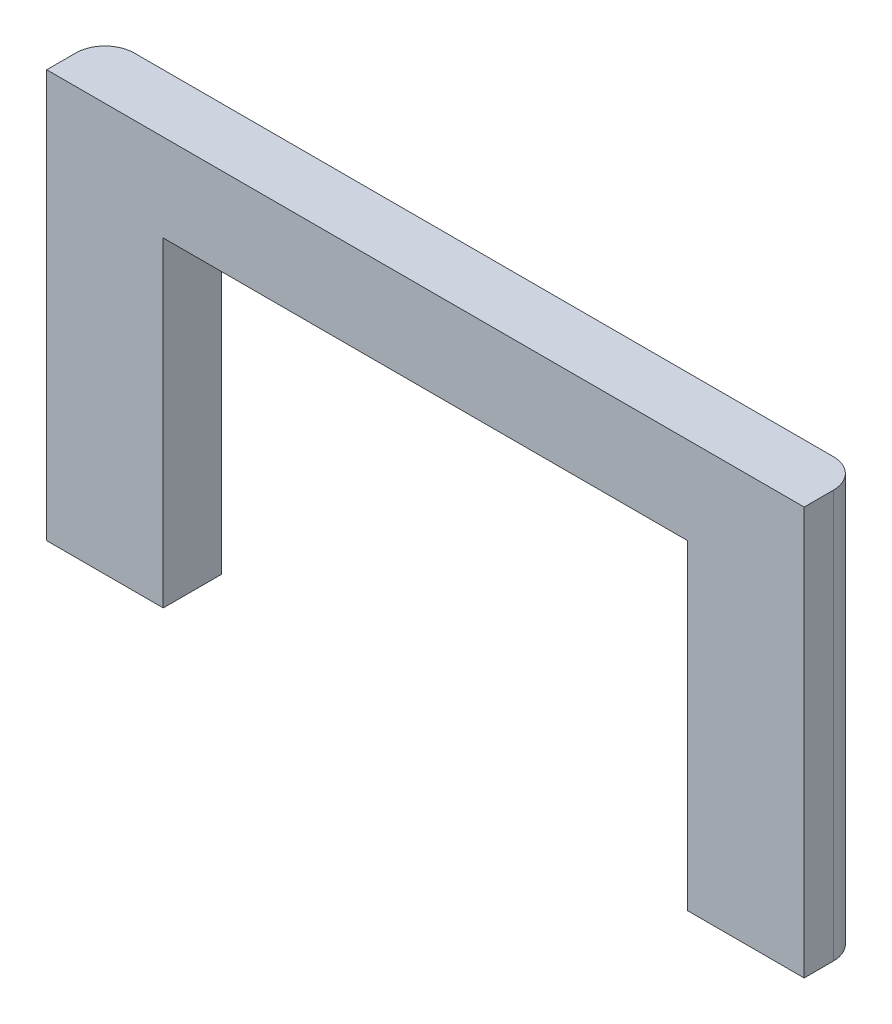
SolidWorks part; units mm, degrees
ref_plane "Front" through (0, 0, 0) normal (0, 0, 1) x (1, 0, 0)
ref_plane "Top" through (0, 0, 0) normal (0, 1, 0) x (1, 0, 0)
ref_plane "Right" through (0, 0, 0) normal (1, 0, 0) x (0, 0, -1)
sketch "Esquisse1" plane through (0, 0, 0) normal (0, 0, 1) x (1, 0, 0)
  line L1 (-83.304, 29.9119) -> (46.696, 29.9119)
  line L2 (-83.304, 29.9119) -> (-83.304, -40.0881)
  line L3 (-83.304, -40.0881) -> (-63.304, -40.0881)
  line L4 (46.696, 29.9119) -> (46.696, -40.0881)
  line L5 (-63.304, 14.9119) -> (26.696, 14.9119)
  line L6 (-63.304, 14.9119) -> (-63.304, -40.0881)
  line L8 (26.696, 14.9119) -> (26.696, -40.0881)
  line L10 (26.696, -40.0881) -> (46.696, -40.0881)
  dimension "D1" = 130
  dimension "D2" = 70
  dimension "D3" = 90
  dimension "D5" = 15
  dimension "D6" = 20
extrude "Boss.-Extru.1" add sketch "Esquisse1" along normal blind 10
fillet "Congé2" radius 5 2 edges at (46.696, -5.0881, 0) (-83.304, -5.0881, 0)
